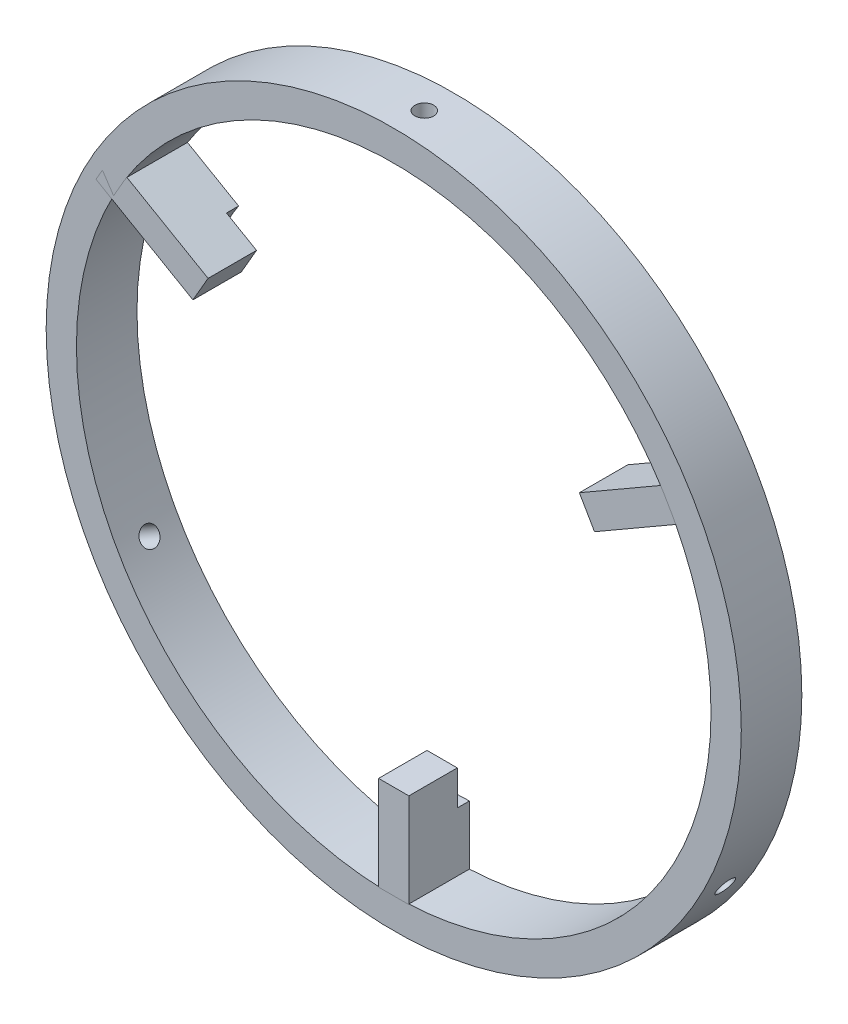
SolidWorks part; units mm, degrees
ref_plane "前视基准面" through (0, 0, 0) normal (0, 0, 1) x (1, 0, 0)
ref_plane "上视基准面" through (0, 0, 0) normal (0, 1, 0) x (1, 0, 0)
ref_plane "右视基准面" through (0, 0, 0) normal (1, 0, 0) x (0, 0, -1)
other "Configuration Table"
sketch "草图1" plane through (0, 0, 0) normal (0, 0, 1) x (1, 0, 0)
  line L0 (31.9122, 18.4245) -> (47.549, 27.4525)
  line L1 (0, -36.8491) -> (0, -52.4073)
  line L2 (-31.9122, 18.4245) -> (-47.9231, 27.6684)
  circle A0 centre (0, 0) radius 36.8491 construction
  circle A1 centre (0, 0) radius 54.9049
  dimension "D1" = 120
  dimension "D2" = 120
extrude "拉伸-薄壁1" add sketch "草图1" along normal blind 10 thin thin type mid plane wall 5
sketch "草图3" plane through (0, 0, 0) normal (0, 1, 0) x (1, 0, 0)
  circle A0 centre (0, -4.9601) radius 1.55
  dimension "D1" = 3.1
extrude "切除-拉伸1" cut sketch "草图3" along normal up to surface (57.4049 mm away)
pattern_circular "阵列(圆周)1" count 3 over 360 about axis through (0, 0, 10) along (0, 0, -1) of "切除-拉伸1"
sketch "草图4" plane through (0, 0, 0) normal (0, 0, -1) x (-1, 0, 0)
  arc A0 (-7.5, 41.833) -> (7.5, 41.833) centre (0, 0) ccw construction
  arc A1 (-7.5, 41.833) -> (7.5, 41.833) centre (0, 0) ccw construction
  arc A2 (-7.5265, 41.9806) -> (7.5265, 41.9806) centre (0, 0) ccw
  dimension "D1" = 0.15
extrude "切除-拉伸-薄壁1" cut sketch "草图4" against normal blind 2 and the other way through all thin thin type one direction reverse wall 6.8
